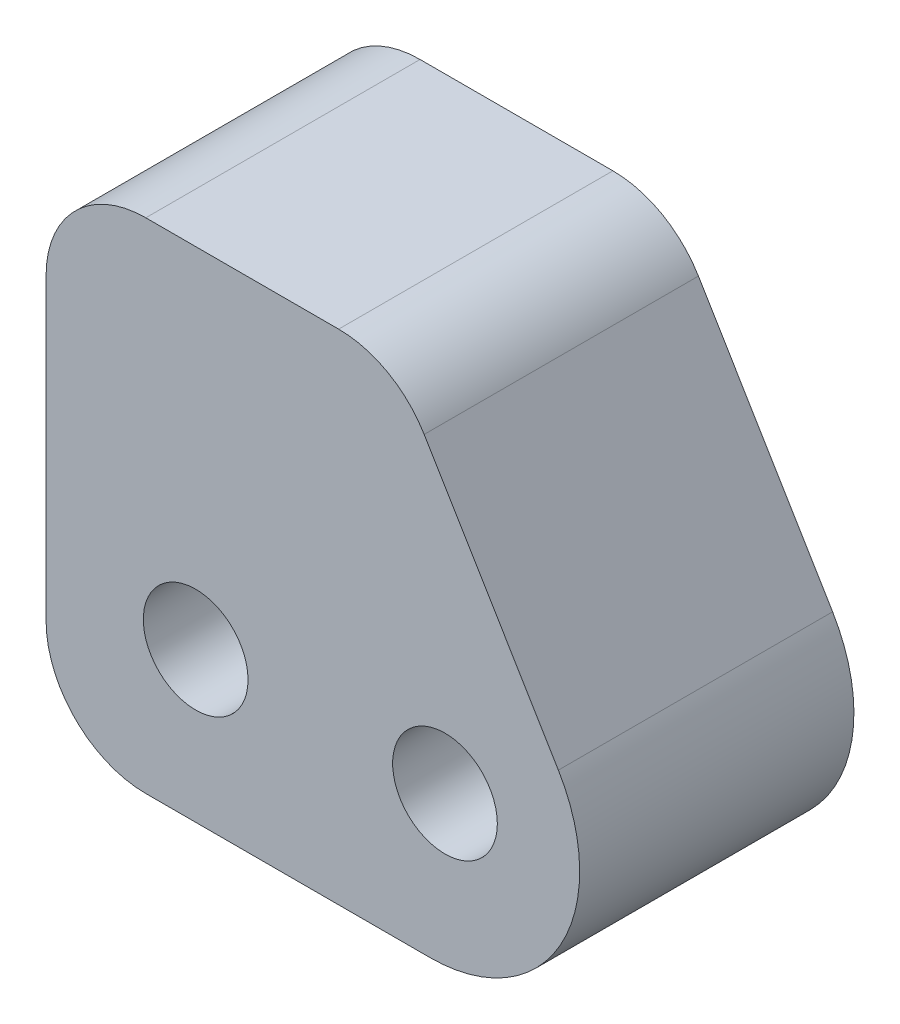
SolidWorks part; units mm, degrees
material "ﾁｰｸ材"
ref_plane "正面" through (0, 0, 0) normal (0, 0, 1) x (1, 0, 0)
ref_plane "平面" through (0, 0, 0) normal (0, 1, 0) x (1, 0, 0)
ref_plane "右側面" through (0, 0, 0) normal (1, 0, 0) x (0, 0, -1)
sketch "ｽｹｯﾁ1" plane through (0, 0, 0) normal (0, 0, 1) x (1, 0, 0)
  line L0 (0, 0) -> (13, 0)
  line L2 (0, 10) -> (0, 0)
  line L3 (0, 10) -> (7, 10)
  line L4 (7, 10) -> (13, 0)
  circle A0 centre (3, 3) radius 1.05
  circle A1 centre (8, 3) radius 1.05
  point P8 (5.1997, 4)
  dimension "D1" = 2.1
  dimension "D3" = 5
  dimension "D2" = 3
  dimension "D4" = 10
  dimension "D5" = 7
  dimension "D6" = 13
  dimension "D7" = 3
extrude "ﾎﾞｽ - 押し出し1" add sketch "ｽｹｯﾁ1" along normal blind 5.5
fillet "ﾌｨﾚｯﾄ1" radius 3 1 edges at (13, 0, 2.75)
fillet "ﾌｨﾚｯﾄ2" radius 2 3 edges at (0, 0, 2.75) (7, 10, 2.75) (0, 10, 2.75)
